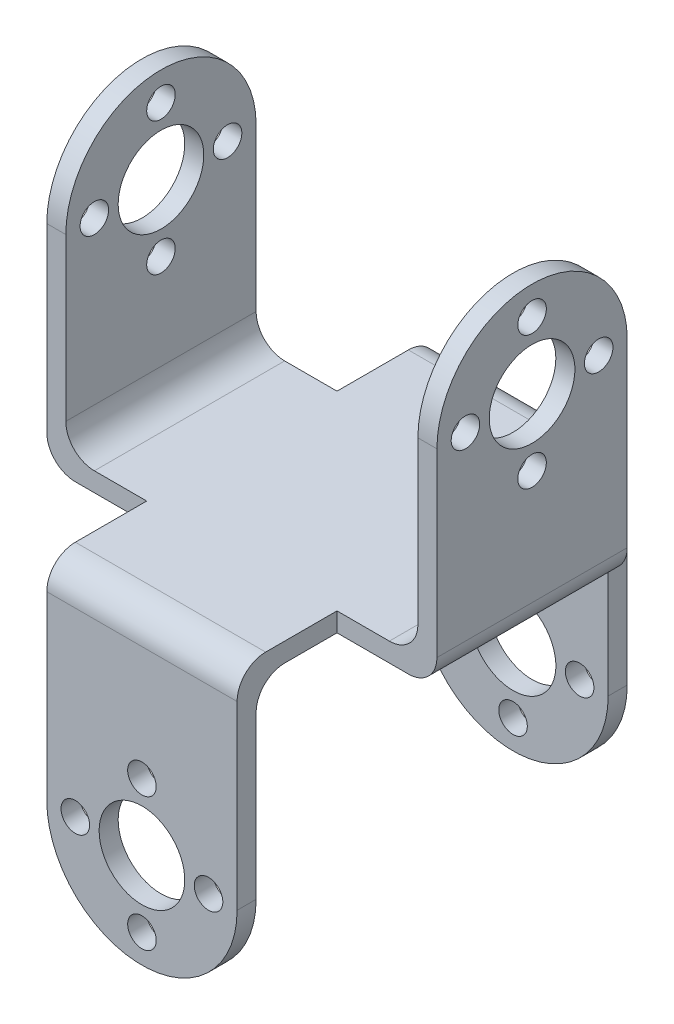
SolidWorks part; units mm, degrees
ref_plane "前视基准面" through (0, 0, 0) normal (0, 0, 1) x (1, 0, 0)
ref_plane "上视基准面" through (0, 0, 0) normal (0, 1, 0) x (1, 0, 0)
ref_plane "右视基准面" through (0, 0, 0) normal (1, 0, 0) x (0, 0, -1)
sketch "草图1" plane through (0, 0, 0) normal (0, 1, 0) x (1, 0, 0)
  line L0 (10, -10) -> (10, -20.5)
  line L1 (-20.5, 10) -> (-10, 10)
  line L2 (-20.5, 10) -> (-20.5, -10)
  line L3 (-20.5, -10) -> (-10, -10)
  line L4 (20.5, 10) -> (20.5, -10)
  line L5 (-20.5, 10) -> (20.5, -10) construction
  line L6 (-20.5, -10) -> (20.5, 10) construction
  line L7 (-10, 20.5) -> (10, 20.5)
  line L8 (-10, 20.5) -> (-10, 10)
  line L9 (-10, -20.5) -> (10, -20.5)
  line L10 (10, 20.5) -> (10, 10)
  line L11 (-10, 20.5) -> (10, -20.5) construction
  line L12 (-10, -20.5) -> (10, 20.5) construction
  line L13 (10, -10) -> (20.5, -10)
  line L14 (-10, -10) -> (-10, -20.5)
  line L15 (10, 10) -> (20.5, 10)
  point P0 (0, 0)
  point P6 (0, 0)
  dimension "D1" = 41
  dimension "D2" = 20
  dimension "D3" = 20
  dimension "D4" = 41
extrude "凸台-拉伸1" add sketch "草图1" along normal blind 2
sketch "草图2" plane through (0, 2, 0) normal (0, 1, 0) x (1, 0, 0)
  line L0 (-20.5, -10) -> (-10, -10) construction
  line L1 (-20.5, 10) -> (-18.5, 10)
  line L2 (-20.5, 10) -> (-20.5, -10)
  line L3 (-20.5, -10) -> (-18.5, -10)
  line L4 (-18.5, 10) -> (-18.5, -10)
  line L5 (10, -10) -> (20.5, -10) construction
  line L6 (20.5, 10) -> (18.5, 10)
  line L7 (20.5, 10) -> (20.5, -10)
  line L8 (20.5, -10) -> (18.5, -10)
  line L9 (18.5, 10) -> (18.5, -10)
  dimension "D1" = 2
  dimension "D2" = 2
extrude "凸台-拉伸2" add sketch "草图2" along normal blind 40
fillet "圆角1" radius 3 4 edges at (-20.5, 0, 0) (-18.5, 2, 0) (18.5, 2, 0) (20.5, 0, 0)
sketch "草图4" plane through (0, 0, 0) normal (0, -1, 0) x (1, 0, 0)
  line L0 (10, 20.5) -> (10, 10) construction
  line L1 (-10, 20.5) -> (10, 20.5)
  line L2 (-10, 20.5) -> (-10, 18.5)
  line L3 (-10, 18.5) -> (10, 18.5)
  line L4 (10, 20.5) -> (10, 18.5)
  line L5 (-10, -20.5) -> (-10, -10) construction
  line L6 (10, -20.5) -> (-10, -20.5)
  line L7 (10, -20.5) -> (10, -18.5)
  line L8 (10, -18.5) -> (-10, -18.5)
  line L9 (-10, -20.5) -> (-10, -18.5)
  dimension "D1" = 2
  dimension "D2" = 2
extrude "凸台-拉伸3" add sketch "草图4" along normal blind 40
fillet "圆角2" radius 3 4 edges at (0, 0, -18.5) (0, 2, -20.5) (0, 2, 20.5) (0, 0, 18.5)
sketch "草图5" plane through (0, 0, -20.5) normal (0, 0, -1) x (-1, 0, 0)
  line L0 (0, -46.7705) -> (0, 23.5536) construction
  line L1 (-25.8926, 0) -> (22.9009, 0) construction
  line L2 (10, -1) -> (10, -40) construction
  line L3 (-10, -1) -> (-10, -40) construction
  line L4 (-10, -20) -> (-10, -40)
  line L5 (-10, -40) -> (10, -40)
  line L6 (10, -40) -> (10, -20)
  arc A0 (10, -20) -> (-10, -20) centre (0, -20) cw
  circle A1 centre (0, -20) radius 4.5
  circle A2 centre (0, -20) radius 7 construction
  circle A3 centre (0, -13) radius 1.5
  circle A4 centre (7, -20) radius 1.5
  circle A5 centre (0, -27) radius 1.5
  circle A6 centre (-7, -20) radius 1.5
  point P29 (0, -20)
  dimension "D2" = 9
  dimension "D3" = 14
  dimension "D4" = 3
  dimension "D1" = 20
  dimension "D5" = 4
extrude "切除-拉伸1" cut sketch "草图5" against normal through all
sketch "草图6" plane through (-20.5, 0, 0) normal (-1, 0, 0) x (0, 0, 1)
  line L0 (0, 47.2402) -> (0, -12.4121) construction
  line L1 (26.009, 2) -> (-24.6618, 2) construction
  line L2 (-10, 42) -> (-10, 3) construction
  line L3 (10, 42) -> (10, 3) construction
  line L4 (-10, 22) -> (-10, 42)
  line L5 (-10, 42) -> (10, 42)
  line L6 (10, 42) -> (10, 22)
  arc A0 (-10, 22) -> (10, 22) centre (0, 22) cw
  circle A1 centre (0, 22) radius 4.5
  circle A2 centre (0, 22) radius 7 construction
  circle A3 centre (0, 15) radius 1.5
  circle A4 centre (-7, 22) radius 1.5
  circle A5 centre (0, 29) radius 1.5
  circle A6 centre (7, 22) radius 1.5
  point P29 (0, 22)
  dimension "D2" = 9
  dimension "D4" = 14
  dimension "D5" = 3
  dimension "D1" = 2
  dimension "D3" = 20
  dimension "D6" = 4
extrude "切除-拉伸2" cut sketch "草图6" against normal through all
